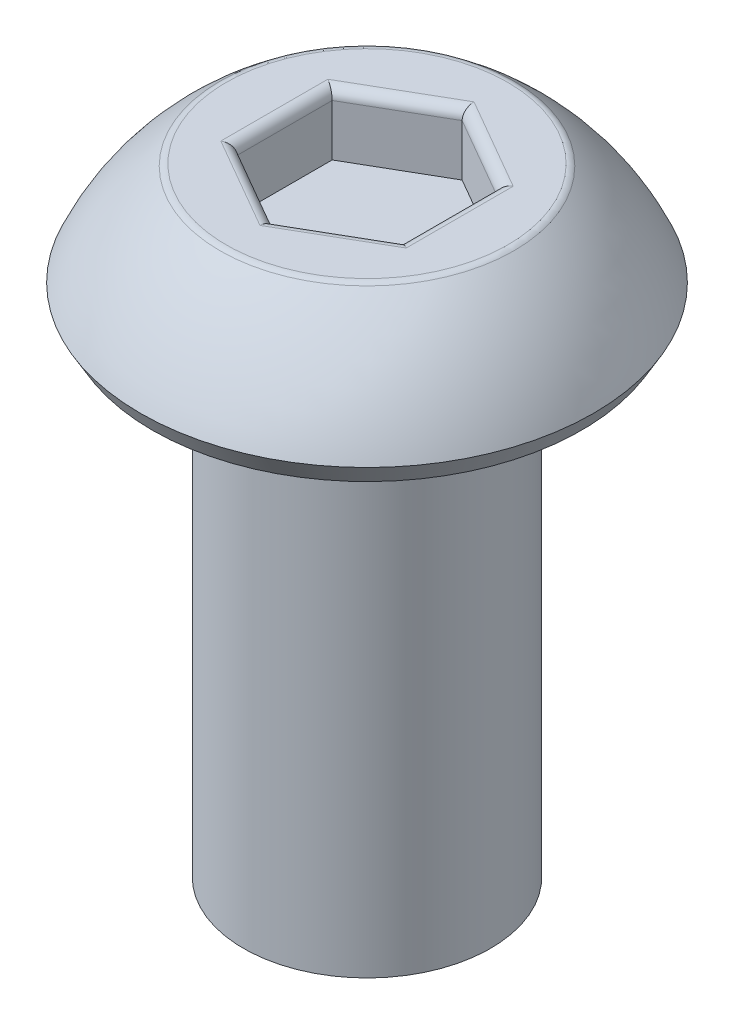
SolidWorks part; units mm, degrees
ref_plane "Front Plane" through (0, 0, 0) normal (0, 0, 1) x (1, 0, 0)
ref_plane "Top Plane" through (0, 0, 0) normal (0, 1, 0) x (1, 0, 0)
ref_plane "Right Plane" through (0, 0, 0) normal (1, 0, 0) x (0, 0, -1)
sketch "Sketch1" plane through (0, 0, 0) normal (1, 0, 0) x (0, 0, -1)
  line L0 (0, 0) -> (0, 1.5) construction
  line L1 (0, 1.5) -> (-1.75, 1.5)
  line L3 (-2.75, 0.25) -> (-2.6057, 0)
  line L4 (-2.6057, 0) -> (-1.5, 0)
  line L5 (-1.5, 0) -> (-1.5, -6)
  line L6 (-1.5, -6) -> (0, -6)
  line L7 (0, -6) -> (0, 1.5)
  line L8 (0, 0) -> (-1.5, 0) construction
  arc A0 (-1.75, 1.5) -> (-2.75, 0.25) centre (0.0077, -0.9312) ccw
  dimension "D5" = 3
  dimension "D1" = 1.5
  dimension "D2" = 2.75
  dimension "D3" = 1.75
  dimension "D4" = 0.25
  dimension "D6" = 60
  dimension "D7" = 1.5
  dimension "D8" = 6
revolve "Revolve1" add sketch "Sketch1" angle 360 about L7
sketch "Sketch2" plane through (0, 1.5, 0) normal (0, 1, 0) x (1, 0, 0)
  line L1 (0, 1.1547) -> (-1, 0.5774)
  line L2 (-1, 0.5774) -> (-1, -0.5774)
  line L3 (-1, -0.5774) -> (0, -1.1547)
  line L4 (0, -1.1547) -> (1, -0.5774)
  line L5 (1, -0.5774) -> (1, 0.5774)
  line L6 (1, 0.5774) -> (0, 1.1547)
  circle A0 centre (0, 0) radius 1 construction
  dimension "D1" = 2
extrude "Cut-Extrude1" cut sketch "Sketch2" against normal blind 0.75
fillet "Fillet1" radius 0.125 7 edges at (0, 1.5, -1.75) (-0.5, 1.5, 0.866) (0.5, 1.5, 0.866) (1, 1.5, 0) (0.5, 1.5, -0.866) (-0.5, 1.5, -0.866) (-1, 1.5, 0)
